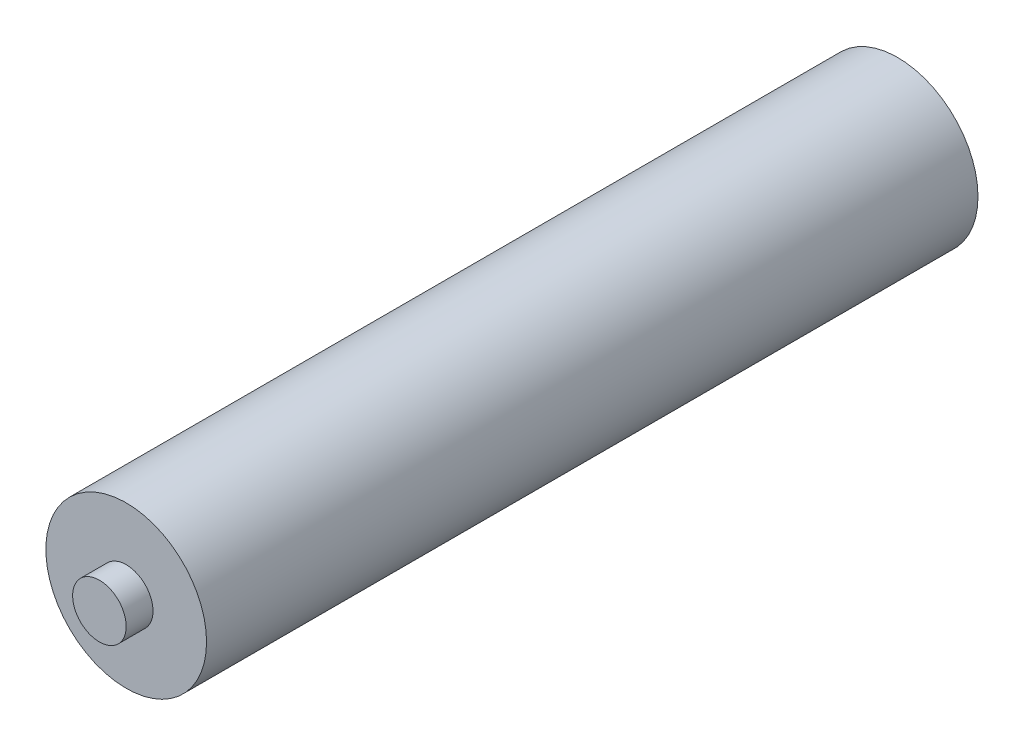
SolidWorks part; units mm, degrees
material "SANTOPRENE"
ref_plane "Front Plane" through (0, 0, 0) normal (0, 0, 1) x (1, 0, 0)
ref_plane "Top Plane" through (0, 0, 0) normal (0, 1, 0) x (1, 0, 0)
ref_plane "Right Plane" through (0, 0, 0) normal (1, 0, 0) x (0, 0, -1)
sketch "Sketch1" plane through (0, 0, 0) normal (0, 0, 1) x (1, 0, 0)
  circle A0 centre (0, 0) radius 15
extrude "Boss-Extrude1" add sketch "Sketch1" along normal blind 144
sketch "Sketch2" plane through (0, 0, 144) normal (0, 0, 1) x (1, 0, 0)
  circle A1 centre (0, 0) radius 5
extrude "Boss-Extrude2" add sketch "Sketch2" along normal blind 5
sketch "Sketch3" plane through (0, 0, 0) normal (0, 0, -1) x (-1, 0, 0)
  circle A0 centre (0, 0) radius 5
extrude "Boss-Extrude3" add sketch "Sketch3" along normal blind 5
